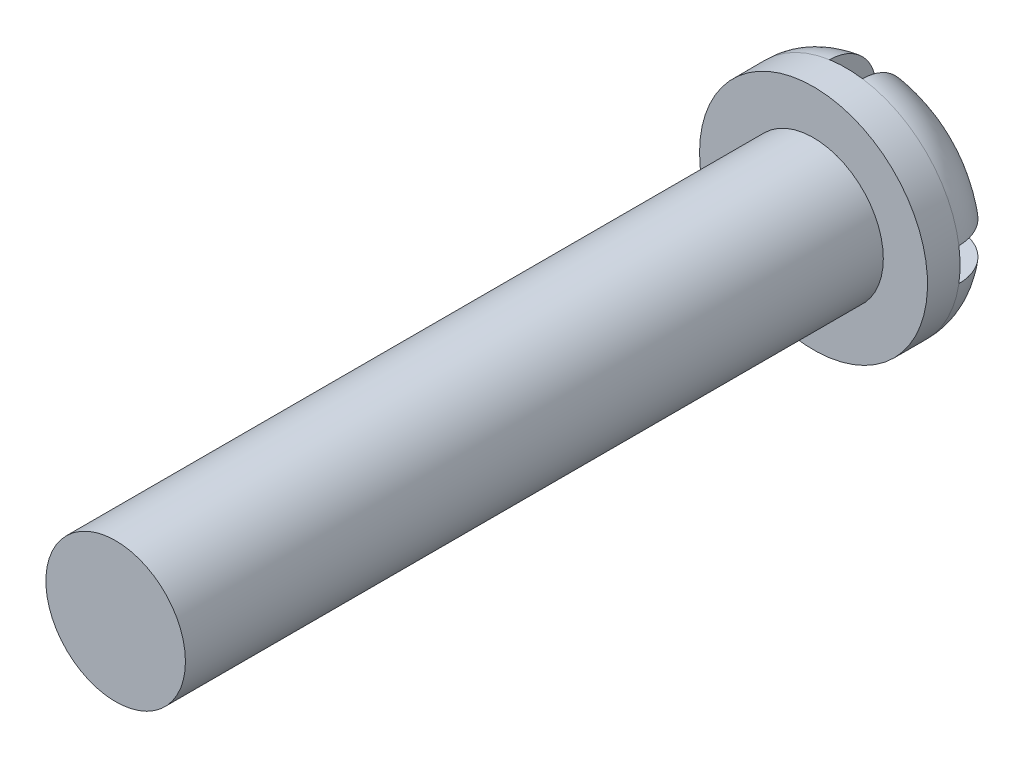
SolidWorks part; units mm, degrees
ref_plane "前视基准面" through (0, 0, 0) normal (0, 0, 1) x (1, 0, 0)
ref_plane "上视基准面" through (0, 0, 0) normal (0, 1, 0) x (1, 0, 0)
ref_plane "右视基准面" through (0, 0, 0) normal (1, 0, 0) x (0, 0, -1)
sketch "草图1" plane through (0, 0, 0) normal (0, 0, 1) x (1, 0, 0)
  circle A0 centre (0, 0) radius 3
extrude "凸台-拉伸1" add sketch "草图1" along normal blind 30
sketch "草图2" plane through (0, 0, 0) normal (0, 0, -1) x (-1, 0, 0)
  circle A0 centre (0, 0) radius 4.9
  dimension "D1" = 9.8
extrude "凸台-拉伸2" add sketch "草图2" along normal blind 3.4
fillet "圆角1" radius 2 1 edges at (-4.9, 0, -3.4)
sketch "草图3" plane through (0, 0, -3.4) normal (0, 0, -1) x (-1, 0, 0)
  line L0 (-0.7071, 0.7071) -> (-0.7071, 6.0064)
  line L1 (1, -1) -> (-1, -1) construction
  line L2 (1, -1) -> (1, 1) construction
  line L3 (1, 1) -> (-1, 1) construction
  line L4 (-1, -1) -> (-1, 1) construction
  line L5 (1, -1) -> (-1, 1) construction
  line L6 (1, 1) -> (-1, -1) construction
  line L7 (0.7071, 0.7071) -> (0.7071, 6.0064)
  line L8 (0.7071, 6.0064) -> (-0.7071, 6.0064)
  line L9 (0.7071, 0.7071) -> (6.0064, 0.7071)
  line L10 (0.7071, -0.7071) -> (6.0064, -0.7071)
  line L11 (6.0064, -0.7071) -> (6.0064, 0.7071)
  line L12 (0.7071, -0.7071) -> (0.7071, -6.0064)
  line L13 (-0.7071, -0.7071) -> (-0.7071, -6.0064)
  line L14 (-0.7071, -6.0064) -> (0.7071, -6.0064)
  line L15 (-0.7071, -0.7071) -> (-6.0064, -0.7071)
  line L16 (-0.7071, 0.7071) -> (-6.0064, 0.7071)
  line L17 (-6.0064, 0.7071) -> (-6.0064, -0.7071)
  circle A0 centre (0, 0) radius 1 construction
  dimension "D1" = 4
extrude "切除-拉伸1" cut sketch "草图3" against normal blind 2
